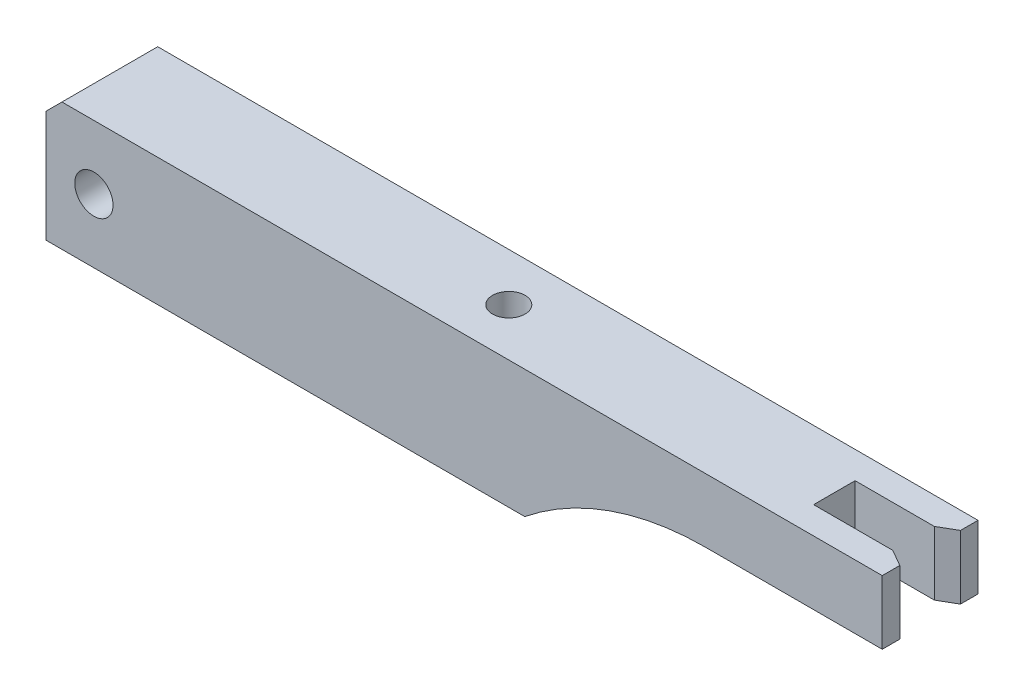
SolidWorks part; units mm, degrees
ref_plane "Front Plane" through (0, 0, 0) normal (0, 0, 1) x (1, 0, 0)
ref_plane "Top Plane" through (0, 0, 0) normal (0, 1, 0) x (1, 0, 0)
ref_plane "Right Plane" through (0, 0, 0) normal (1, 0, 0) x (0, 0, -1)
sketch "Sketch1" plane through (0, 0, 0) normal (0, 0, 1) x (1, 0, 0)
  line L0 (20, 0) -> (-130, 0)
  line L1 (-130, 0) -> (-130, 40)
  line L2 (-130, 40) -> (132, 40)
  line L3 (132, 40) -> (132, 20)
  line L4 (132, 20) -> (76.5685, 20)
  arc A0 (76.5685, 20) -> (20, 0) centre (76.5685, -70) ccw
  dimension "D5" = 90
  dimension "D1" = 130
  dimension "D2" = 262
  dimension "D3" = 40
  dimension "D4" = 20
  dimension "D6" = 150
extrude "main body" add sketch "Sketch1" along normal mid plane 30
hole_wizard "Ø12.0 (12) Diameter Hole1" positions "3DSketch1" profile "Sketch2" hole size "Ø12.0" standard "Ansi Metric" end condition through all
sketch3d "3DSketch1"
  line L0 (-130, 40, 15) -> (-130, 0, 15) construction
  point P0 (-115, 20, 15)
  dimension "D1" = 15
sketch "Sketch2" plane through (-115, 20, 15) normal (1, 0, 0) x (0, -1, 0)
  line L0 (0, 0) -> (0, 30)
  line L1 (0, 30) -> (6, 30)
  line L2 (6, 30) -> (6, 0)
  line L5 (6, 0) -> (0, 0)
  line L11 (0, -6.35) -> (0, 107.95) construction
  dimension "Thru Hole Dia." = 12
  dimension "Thru Hole Depth" = 30
hole_wizard "M12x1.75 Tapped Hole2" positions "Sketch6" profile "Sketch5" tap size "M12x1.75" standard "Ansi Metric" end condition through all
sketch "Sketch6" plane through (0, 40, 0) normal (0, 1, 0) x (-1, 0, 0)
  point P0 (0, 0)
cosmetic thread "Hole Thread3" parameters "D2"=12
sketch "Sketch5" plane through (0, 40, 0) normal (1, 0, 0) x (0, 0, 1)
  line L0 (0, 0) -> (0, 40)
  line L1 (0, 40) -> (5.1, 40)
  line L2 (5.1, 40) -> (5.1, 0)
  line L5 (5.1, 0) -> (0, 0)
  line L11 (0, -6.35) -> (0, 107.95) construction
  dimension "Thru Tap Drill Dia." = 10.2
  dimension "Thru Tap Drill Depth" = 40
sketch "Sketch4" plane through (0, 40, 0) normal (0, 1, 0) x (1, 0, 0)
  line L0 (132, -15) -> (132, 15) construction
  line L1 (102, -6.5) -> (132, -6.5)
  line L2 (102, -6.5) -> (102, 6.5)
  line L3 (102, 6.5) -> (132, 6.5)
  line L4 (132, -6.5) -> (132, 6.5)
  line L5 (102, 0) -> (132, 0) construction
  dimension "D1" = 30
  dimension "D2" = 13
extrude "cut out" cut sketch "Sketch4" against normal through all
chamfer "C'FER 5 x 45" distance 5 angle 45 1 edges at (-130, 40, 0)
chamfer "C'FER 3 x 30" distance 3 angle 60 2 edges at (132, 30, -6.5) (132, 30, 6.5)
